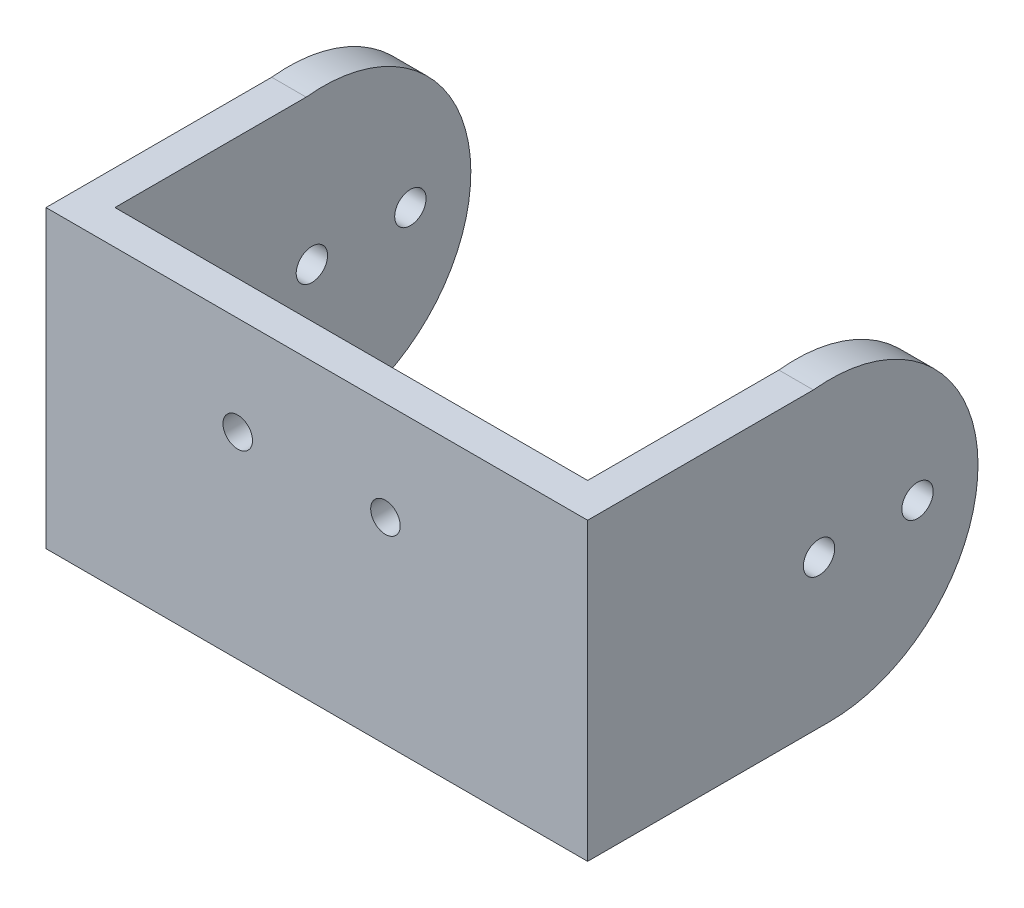
SolidWorks part; units mm, degrees
ref_plane "前视基准面" through (0, 0, 0) normal (0, 0, 1) x (1, 0, 0)
ref_plane "上视基准面" through (0, 0, 0) normal (0, 1, 0) x (1, 0, 0)
ref_plane "右视基准面" through (0, 0, 0) normal (1, 0, 0) x (0, 0, -1)
sketch "草图1" plane through (0, 0, 0) normal (0, 0, 1) x (1, 0, 0)
  line L1 (27.5, -15) -> (-27.5, -15)
  line L2 (27.5, -15) -> (27.5, 15)
  line L3 (27.5, 15) -> (-27.5, 15)
  line L4 (-27.5, -15) -> (-27.5, 15)
  point P0 (0, 0)
  dimension "D1" = 30
  dimension "D2" = 55
extrude "凸台-拉伸1" add sketch "草图1" along normal blind 3.5
ref_plane "基准面1" through (27.5, 0, 0) normal (1, 0, 0) x (0, 0, -1)
sketch "草图2" plane through (27.5, 0, 0) normal (1, 0, 0) x (0, 0, -1)
  line L0 (0, 15) -> (0, -15)
  line L1 (0, -15) -> (0, 15) construction
  line L2 (0, -15) -> (21, -15)
  line L4 (19.4198, 15) -> (0, 15)
  arc A0 (19.4198, 15) -> (21, -15) centre (21.093, 0.0465) cw
  circle A2 centre (20, 0) radius 1.5927
  circle A3 centre (20, 0) radius 10 construction
  circle A15 centre (30, 0) radius 1.5927
  dimension "D7" = 20
extrude "凸台-拉伸2" add sketch "草图2" against normal blind 3.5
mirror "镜向1" about plane through (0, 0, 0) normal (1, 0, 0) of "凸台-拉伸2"
sketch "草图3" plane through (0, 0, 3.5) normal (0, 0, 1) x (1, 0, 0)
  line L1 (-33.8419, 0) -> (30.3788, 0) construction
  line L2 (27.5, 15) -> (-27.5, 15) construction
  circle A2 centre (6.97, 4.99) radius 1.5
  circle A3 centre (-8.03, 4.99) radius 1.5
  dimension "D1" = 15
  dimension "D2" = 3
  dimension "D3" = 3
  dimension "D5" = 10.01
extrude "切除-拉伸1" cut sketch "草图3" against normal blind 3.5
